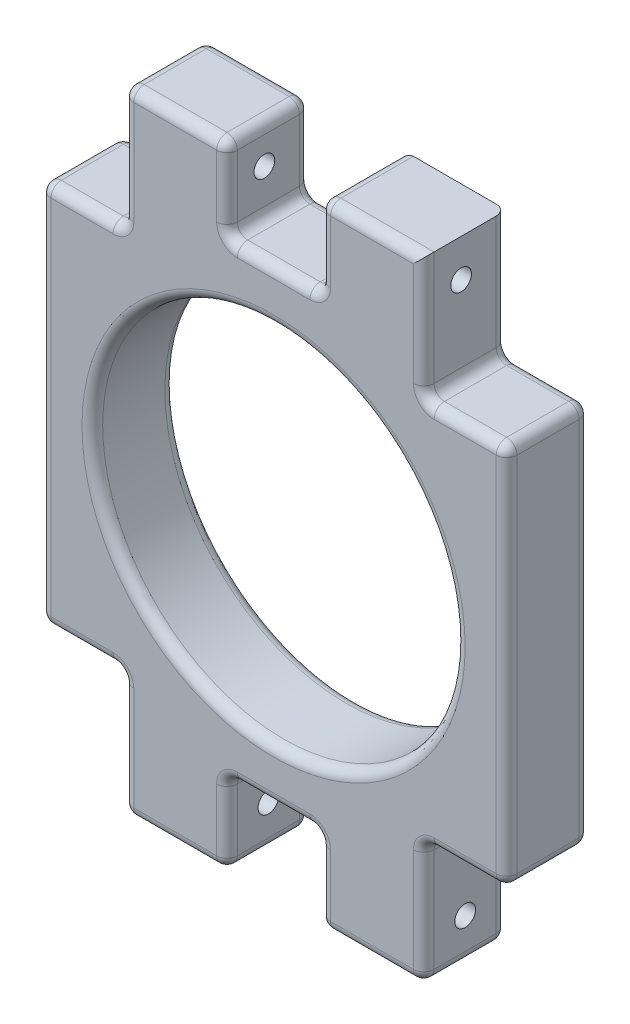
SolidWorks part; units mm, degrees
ref_plane "Front Plane" through (0, 0, 0) normal (0, 0, 1) x (1, 0, 0)
ref_plane "Top Plane" through (0, 0, 0) normal (0, 1, 0) x (1, 0, 0)
ref_plane "Right Plane" through (0, 0, 0) normal (1, 0, 0) x (0, 0, -1)
sketch "Sketch2" plane through (0, 0, 0) normal (0, 0, 1) x (1, 0, 0)
  line L0 (-22.5, 0) -> (0, 0) construction
  line L6 (-14.5, 22.5) -> (14.5, 22.5) construction
  line L7 (0, 22.5) -> (0, -22.5) construction
  line L12 (-14.5, 22.5) -> (-14.5, 30.5)
  line L13 (-14.5, 30.5) -> (-4.5, 30.5)
  line L14 (-4.5, 30.5) -> (-4.5, 22.5)
  line L15 (22.5, 18.5) -> (22.5, -18.5)
  line L16 (14.5, 30.5) -> (4.5, 30.5)
  line L17 (4.5, 30.5) -> (4.5, 22.5)
  line L18 (14.5, 22.5) -> (14.5, 18.5)
  line L19 (14.5, 18.5) -> (22.5, 18.5)
  line L20 (14.5, 22.5) -> (14.5, 18.5)
  line L21 (14.5, 22.5) -> (14.5, 30.5)
  line L22 (-14.5, -22.5) -> (-14.5, -18.5)
  line L23 (-14.5, -18.5) -> (-22.5, -18.5)
  line L24 (-14.5, 22.5) -> (-14.5, 18.5)
  line L25 (-14.5, 18.5) -> (-22.5, 18.5)
  line L26 (-22.5, 18.5) -> (-22.5, -18.5)
  line L27 (-14.5, 22.5) -> (-14.5, 18.5)
  line L28 (-14.5, -22.5) -> (-14.5, -18.5)
  line L29 (14.5, -22.5) -> (14.5, -30.5)
  line L30 (14.5, -22.5) -> (14.5, -18.5)
  line L31 (14.5, -18.5) -> (22.5, -18.5)
  line L32 (14.5, -22.5) -> (14.5, -18.5)
  line L33 (4.5, -30.5) -> (4.5, -22.5)
  line L34 (14.5, -30.5) -> (4.5, -30.5)
  line L35 (-4.5, -30.5) -> (-4.5, -22.5)
  line L36 (-14.5, -30.5) -> (-4.5, -30.5)
  line L37 (-14.5, -22.5) -> (-14.5, -30.5)
  line L38 (-14.5, -22.5) -> (14.5, -22.5) construction
  line L39 (-4.5, 22.5) -> (4.5, 22.5)
  line L40 (-4.5, -22.5) -> (4.5, -22.5)
  circle A0 centre (0, 0) radius 17.5
  point P0 (0, 0)
  point P31 (22.5, 0)
  dimension "D3" = 35
  dimension "D1" = 8
  dimension "D2" = 10
  dimension "D4" = 4
  dimension "D5" = 14.5
  dimension "D6" = 8
  dimension "D7" = 18.5
extrude "Boss-Extrude1" add sketch "Sketch2" along normal blind 8
sketch "Sketch4" plane through (0, 0, 8) normal (0, 0, 1) x (1, 0, 0)
  line L0 (0, 0) -> (42.0958, 0) construction
  circle A0 centre (0, 14.5) radius 3
  circle A2 centre (0, -14.5) radius 3
  dimension "D1" = 6
  dimension "D3" = 14.5
extrude "Cut-Extrude2" [suppressed] cut sketch "Sketch4" against normal through all both and the other way through all
fillet "Fillet1" radius 1 59 edges at (-18.5, -18.5, 8) (-14.5, -24.5, 8) (-9.5, -30.5, 8) (-4.5, -26.5, 8) (0, -22.5, 8) (4.5, -26.5, 8) (-9.5, -30.5, 0) (-14.5, -24.5, 0) (-18.5, -18.5, 0) (-22.5, 0, 0) (-18.5, 18.5, 0) (-14.5, 24.5, 0) (9.5, -30.5, 8) (-4.5, 26.5, 0) (0, 22.5, 0) (4.5, 26.5, 0) (14.5, 24.5, 0) (18.5, 18.5, 0) (22.5, 0, 0) (18.5, -18.5, 0) (14.5, -24.5, 0) (14.5, -24.5, 8) (9.5, -30.5, 0) (4.5, -26.5, 0) (0, -22.5, 0) (-4.5, -26.5, 0) (17.5, 0, 0) (18.5, -18.5, 8) (-4.5, -30.5, 4) (-14.5, -30.5, 4) (-14.5, -18.5, 4) (-22.5, -18.5, 4) (-22.5, 18.5, 4) (-14.5, 18.5, 4) (-14.5, 30.5, 4) (-4.5, 30.5, 4) (-4.5, 22.5, 4) (4.5, 22.5, 4) (4.5, 30.5, 4) (14.5, 18.5, 4) (22.5, 18.5, 4) (22.5, -18.5, 4) (14.5, -18.5, 4) (14.5, -30.5, 4) (4.5, -30.5, 4) (4.5, -22.5, 4) (-4.5, -22.5, 4) (22.5, 0, 8) (18.5, 18.5, 8) (14.5, 24.5, 8) (9.5, 30.5, 8) (4.5, 26.5, 8) (17.5, 0, 8) (0, 22.5, 8) (-4.5, 26.5, 8) (-9.5, 30.5, 8) (-14.5, 24.5, 8) (-18.5, 18.5, 8) (-22.5, 0, 8)
sketch "Sketch5" plane through (-4.5, 0, 0) normal (1, 0, 0) x (0, 0, -1)
  circle A0 centre (-4.3896, 26.8606) radius 1
  dimension "D1" = 2
extrude "Cut-Extrude3" cut sketch "Sketch5" against normal through all both and the other way through all
sketch "Sketch6" plane through (-4.5, 0, 0) normal (1, 0, 0) x (0, 0, -1)
  circle A0 centre (-4, -26.5) radius 1
  dimension "D1" = 2
extrude "Cut-Extrude4" cut sketch "Sketch6" against normal through all both and the other way through all
